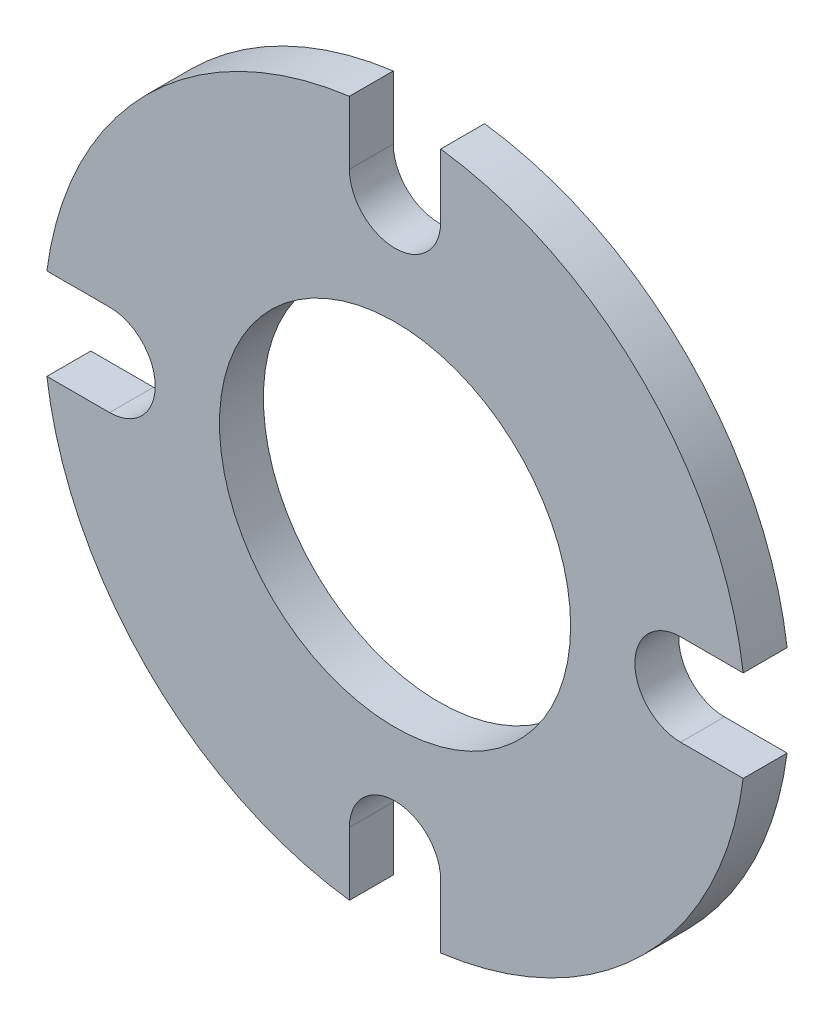
SolidWorks part; units mm, degrees
ref_plane "Front Plane" through (0, 0, 0) normal (0, 0, 1) x (1, 0, 0)
ref_plane "Top Plane" through (0, 0, 0) normal (0, 1, 0) x (1, 0, 0)
ref_plane "Right Plane" through (0, 0, 0) normal (1, 0, 0) x (0, 0, -1)
sketch "Sketch1" plane through (0, 0, 0) normal (0, 0, 1) x (1, 0, 0)
  line L0 (0, 0) -> (0, 998.8973) construction
  line L1 (0, 0) -> (998.8973, 0) construction
  line L2 (0.9915, 0.13) -> (0.813, 0.13)
  line L3 (0.813, -0.13) -> (0.9915, -0.13)
  line L4 (-0.813, -0.13) -> (-0.9915, -0.13)
  line L5 (-0.9915, 0.13) -> (-0.813, 0.13)
  line L6 (-0.13, -0.9915) -> (-0.13, -0.8115)
  line L7 (0.13, -0.9915) -> (0.13, -0.8115)
  line L8 (-0.13, 0.9915) -> (-0.13, 0.8115)
  line L9 (0.13, 0.9915) -> (0.13, 0.8115)
  arc A0 (0.9915, 0.13) -> (0.13, 0.9915) centre (0, 0) ccw construction
  circle A1 centre (0, 0) radius 0.5
  arc A2 (0.813, 0.13) -> (0.813, -0.13) centre (0.813, 0) ccw
  arc A3 (0.9915, 0.13) -> (0.13, 0.9915) centre (0, 0) ccw
  arc A4 (-0.813, 0.13) -> (-0.813, -0.13) centre (-0.813, 0) cw
  arc A5 (-0.9915, -0.13) -> (-0.13, -0.9915) centre (0, 0) ccw construction
  arc A6 (-0.9915, -0.13) -> (-0.13, -0.9915) centre (0, 0) ccw
  arc A7 (-0.13, -0.8115) -> (0.13, -0.8115) centre (0, -0.8115) cw
  arc A8 (0.13, -0.9915) -> (0.9915, -0.13) centre (0, 0) ccw construction
  arc A9 (0.13, -0.9915) -> (0.9915, -0.13) centre (0, 0) ccw
  arc A10 (-0.13, 0.8115) -> (0.13, 0.8115) centre (0, 0.8115) ccw
  arc A11 (-0.13, 0.9915) -> (-0.9915, 0.13) centre (0, 0) ccw construction
  arc A12 (-0.13, 0.9915) -> (-0.9915, 0.13) centre (0, 0) ccw
  point P22 (0, 0)
  point P23 (0, 0)
  dimension "D1" = 2
  dimension "D2" = 1
  dimension "D8" = 0.13
  dimension "D10" = 0.13
  dimension "D3" = 0.26
  dimension "D4" = 0.13
  dimension "D5" = 0.13
  dimension "D6" = 0.813
  dimension "D7" = 0.813
  dimension "D9" = 0.13
  dimension "D11" = 0.1785
  dimension "D12" = 0.18
extrude "Boss-Extrude1" add sketch "Sketch1" along normal mid plane 0.125
